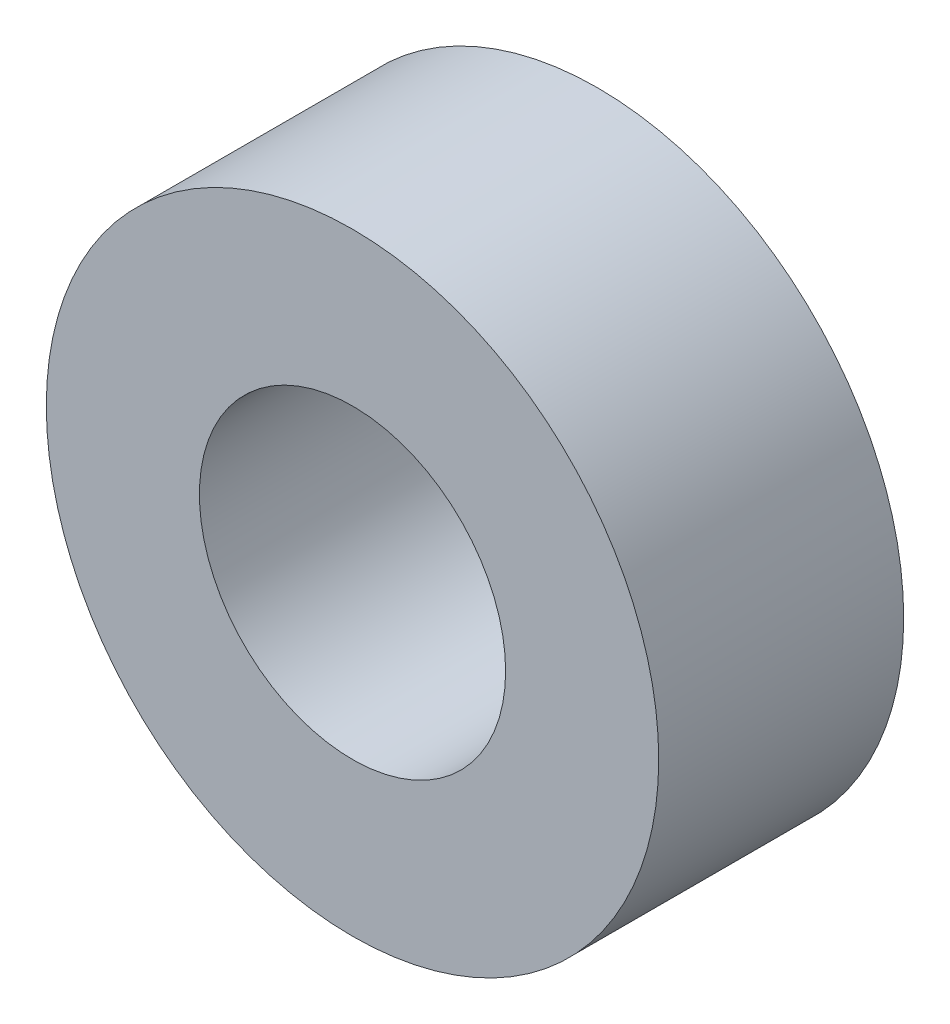
SolidWorks part; units mm, degrees
ref_plane "Front Plane" through (0, 0, 0) normal (0, 0, 1) x (1, 0, 0)
ref_plane "Top Plane" through (0, 0, 0) normal (0, 1, 0) x (1, 0, 0)
ref_plane "Right Plane" through (0, 0, 0) normal (1, 0, 0) x (0, 0, -1)
sketch "Sketch1" plane through (0, 0, 0) normal (0, 0, 1) x (1, 0, 0)
  circle A0 centre (0, 0) radius 1.25
  circle A1 centre (0, 0) radius 0.625
  dimension "D1" = 2.5
  dimension "D2" = 1.25
extrude "Boss-Extrude1" add sketch "Sketch1" along normal blind 1
